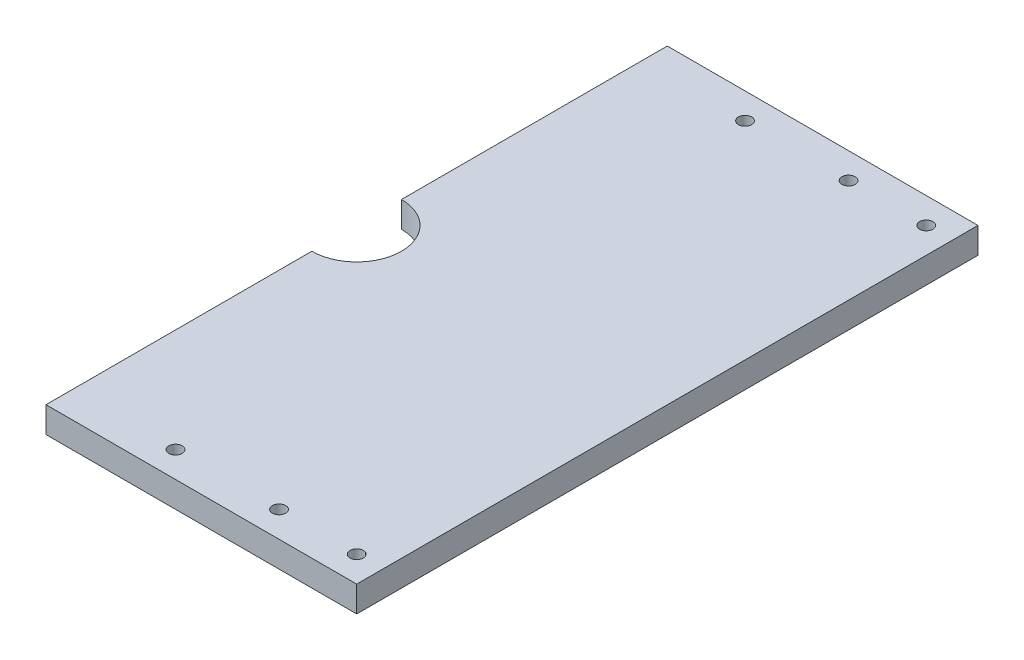
SolidWorks part; units mm, degrees
material "Copper"
ref_plane "Front Plane" through (0, 0, 0) normal (0, 0, 1) x (1, 0, 0)
ref_plane "Top Plane" through (0, 0, 0) normal (0, 1, 0) x (1, 0, 0)
ref_plane "Right Plane" through (0, 0, 0) normal (1, 0, 0) x (0, 0, -1)
sketch "Sketch1" plane through (0, 0, 0) normal (0, 1, 0) x (1, 0, 0)
  line L0 (0, -11) -> (0, -76.2)
  line L1 (0, 76.2) -> (76.22, 76.2)
  line L2 (0, 76.2) -> (0, 11)
  line L3 (0, -76.2) -> (76.22, -76.2)
  line L4 (76.22, 76.2) -> (76.22, -76.2)
  line L5 (0, 0) -> (76.22, 0) construction
  arc A0 (0, -11) -> (0, 11) centre (0, 0) ccw
  circle A1 centre (69.87, 69.85) radius 1.6319
  circle A2 centre (69.87, -69.85) radius 1.6319
  circle A3 centre (50.82, 69.85) radius 1.6319
  circle A4 centre (25.42, 69.85) radius 1.6319
  circle A5 centre (50.82, -69.85) radius 1.6319
  circle A6 centre (25.42, -69.85) radius 1.6319
  dimension "D1" = 11
  dimension "D4" = 3.2639
  dimension "D2" = 76.22
  dimension "D3" = 152.4
  dimension "D5" = 6.35
  dimension "D6" = 6.35
  dimension "D7" = 25.4
  dimension "D8" = 19.05
extrude "Boss-Extrude1" add sketch "Sketch1" along normal blind 6.35
equation "\"D6@Sketch1\"=\"D5@Sketch1\""
